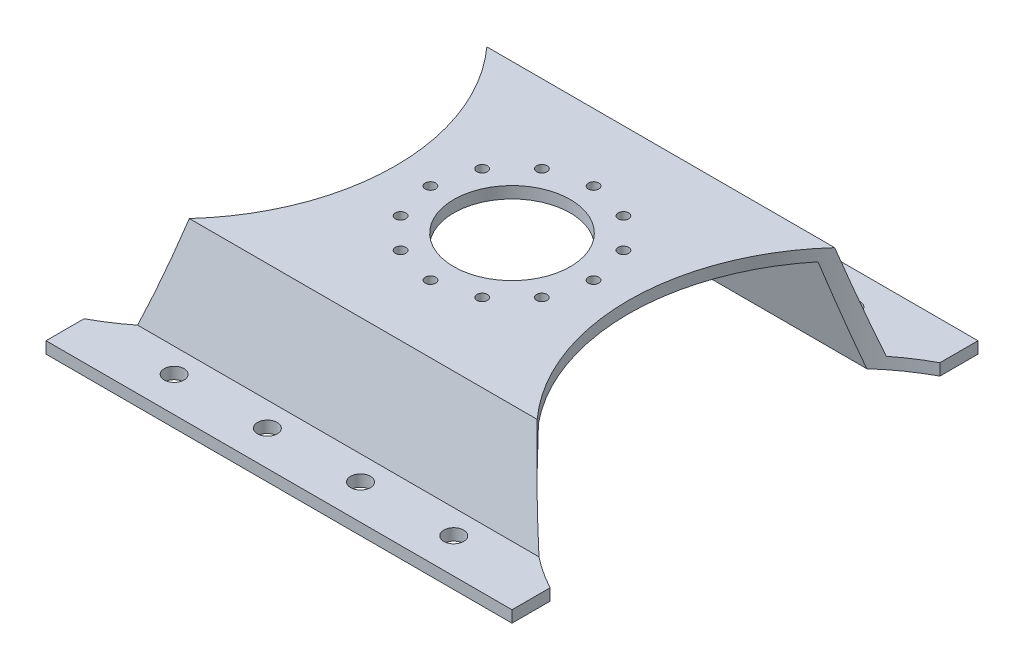
SolidWorks part; units mm, degrees
ref_plane "前视基准面" through (0, 0, 0) normal (0, 0, 1) x (1, 0, 0)
ref_plane "上视基准面" through (0, 0, 0) normal (0, 1, 0) x (1, 0, 0)
ref_plane "右视基准面" through (0, 0, 0) normal (1, 0, 0) x (0, 0, -1)
other "Configuration Table"
sketch "草图1" plane through (0, 0, 0) normal (1, 0, 0) x (0, 0, -1)
  line L0 (-65.366, 0) -> (70.371, 0) construction
  line L1 (0, 65.461) -> (0, -48.1537) construction
  line L2 (-100, 0) -> (-70.718, 0)
  line L3 (-70.718, 0) -> (-60, 40)
  line L4 (-60, 40) -> (60, 40)
  line L5 (-100, 0) -> (-100, 5)
  line L6 (-100, 5) -> (-74.5546, 5)
  line L7 (-74.5546, 5) -> (-63.8366, 45)
  line L8 (-63.8366, 45) -> (63.8366, 45)
  line L9 (74.5546, 5) -> (63.8366, 45)
  line L10 (100, 5) -> (74.5546, 5)
  line L11 (100, 0) -> (100, 5)
  line L12 (70.718, 0) -> (60, 40)
  line L13 (100, 0) -> (70.718, 0)
  point P16 (0, 45)
  point P20 (0, 40)
  dimension "D1" = 5
  dimension "D2" = 5
  dimension "D3" = 5
  dimension "D4" = 90
  dimension "D5" = 100
  dimension "D6" = 75
  dimension "D7" = 60
extrude "凸台-拉伸1" add sketch "草图1" along normal blind 200
sketch "草图2" plane through (0, 45, 0) normal (0, 1, 0) x (1, 0, 0)
  line L0 (-74.6233, 0) -> (250.0124, 0) construction
  line L1 (100, 134.4638) -> (100, -135.2033) construction
  line L4 (200, -74.5546) -> (200, -100) construction
  line L5 (0, -74.5546) -> (0, -100) construction
  circle A0 centre (245, 0) radius 95
  circle A2 centre (-45, 0) radius 95
  dimension "D1" = 190
  dimension "D2" = 145
extrude "切除-拉伸1" cut sketch "草图2" against normal blind 150
sketch "草图3" plane through (0, 5, 0) normal (0, 1, 0) x (1, 0, 0)
  line L0 (100, 150.1163) -> (100, -143.313) construction
  line L1 (0, -83.666) -> (0, -100) construction
  line L2 (200, -83.666) -> (200, -100) construction
  line L3 (0, 0) -> (200.2338, 0) construction
  circle A0 centre (120, -85) radius 4.25
  circle A1 centre (160, -85) radius 4.25
  circle A2 centre (40, -85) radius 4.25
  circle A3 centre (80, -85) radius 4.25
  circle A4 centre (160, 85) radius 4.25
  circle A5 centre (120, 85) radius 4.25
  circle A6 centre (80, 85) radius 4.25
  circle A7 centre (40, 85) radius 4.25
  dimension "D1" = 8.5
  dimension "D2" = 20
  dimension "D3" = 40
  dimension "D4" = 85
extrude "切除-拉伸2" cut sketch "草图3" against normal blind 150
sketch "草图4" plane through (0, 45, 0) normal (0, 1, 0) x (1, 0, 0)
  line L0 (-30.2665, 0) -> (210.7522, 0) construction
  line L1 (100, 139.1719) -> (100, -147.4542) construction
  line L2 (200, -83.666) -> (200, -100) construction
  line L3 (0, -83.666) -> (0, -100) construction
  circle A0 centre (100, 0) radius 35 construction
  circle A1 centre (100, 35) radius 2.25
  circle A2 centre (117.5, 30.3109) radius 2.25
  circle A3 centre (130.3109, 17.5) radius 2.25
  circle A4 centre (135, 0) radius 2.25
  circle A5 centre (130.3109, -17.5) radius 2.25
  circle A6 centre (117.5, -30.3109) radius 2.25
  circle A7 centre (100, -35) radius 2.25
  circle A8 centre (82.5, -30.3109) radius 2.25
  circle A9 centre (69.6891, -17.5) radius 2.25
  circle A10 centre (65, 0) radius 2.25
  circle A11 centre (69.6891, 17.5) radius 2.25
  circle A12 centre (82.5, 30.3109) radius 2.25
  circle A13 centre (100, 0) radius 25
  point P37 (100, 0)
  dimension "D1" = 70
  dimension "D2" = 4.5
  dimension "D4" = 50
  dimension "D3" = 12
extrude "切除-拉伸3" cut sketch "草图4" against normal blind 10
